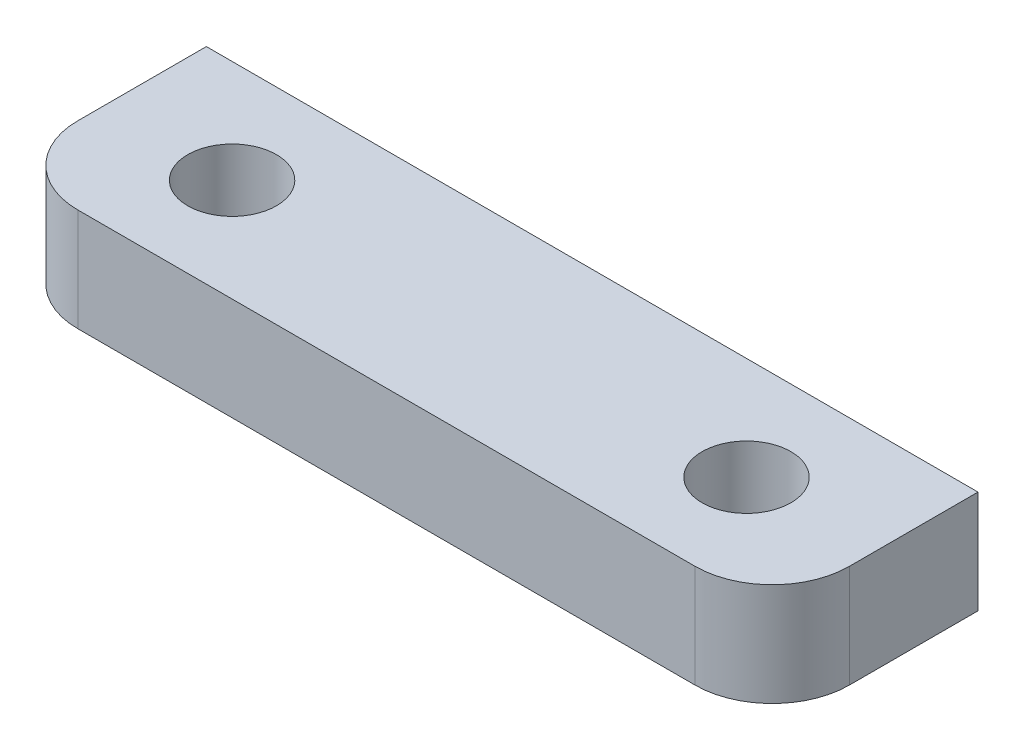
SolidWorks part; units mm, degrees
ref_plane "Front Plane" through (0, 0, 0) normal (0, 0, 1) x (1, 0, 0)
ref_plane "Top Plane" through (0, 0, 0) normal (0, 1, 0) x (1, 0, 0)
ref_plane "Right Plane" through (0, 0, 0) normal (1, 0, 0) x (0, 0, -1)
sketch "Sketch1" plane through (0, 0, 0) normal (0, 1, 0) x (1, 0, 0)
  line L0 (0, 0) -> (20, 0) construction
  line L2 (-5, -4) -> (25, -4)
  line L3 (-5, -4) -> (-5, 4)
  line L4 (-5, 4) -> (25, 4)
  line L5 (25, -4) -> (25, 4)
  line L6 (-5, -4) -> (25, 4) construction
  line L7 (-5, 4) -> (25, -4) construction
  circle A0 centre (0, 0) radius 1.725
  circle A1 centre (20, 0) radius 1.725
  point P5 (10, 0)
extrude "Boss-Extrude1" add sketch "Sketch1" along normal blind 4
fillet "Fillet1" radius 3 2 edges at (25, 2, 4) (-5, 2, 4)
